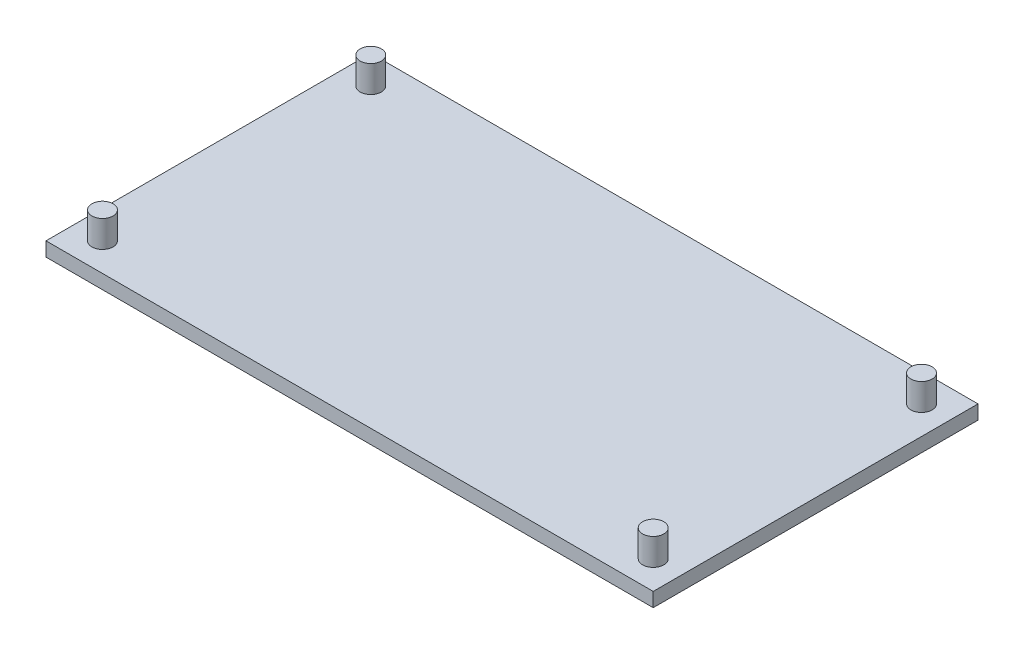
SolidWorks part; units mm, degrees
ref_plane "前视基准面" through (0, 0, 0) normal (0, 0, 1) x (1, 0, 0)
ref_plane "上视基准面" through (0, 0, 0) normal (0, 1, 0) x (1, 0, 0)
ref_plane "右视基准面" through (0, 0, 0) normal (1, 0, 0) x (0, 0, -1)
other "Configuration Table"
sketch "草图1" plane through (0, 0, 0) normal (0, 1, 0) x (1, 0, 0)
  line L5 (-43, -23) -> (43, -23)
  line L6 (-43, -23) -> (-43, 23)
  line L7 (-43, 23) -> (43, 23)
  line L8 (43, -23) -> (43, 23)
  line L9 (-43, -23) -> (43, 23) construction
  line L10 (-43, 23) -> (43, -23) construction
  point P0 (0, 0)
  dimension "D1" = 86
  dimension "D2" = 46
extrude "凸台-拉伸1" add sketch "草图1" along normal blind 2
sketch "草图2" plane through (0, 0, 0) normal (0, -1, 0) x (1, 0, 0)
  circle A0 centre (-39, 19) radius 1.5
  circle A1 centre (-39, -19) radius 1.5
  circle A2 centre (39, 19) radius 1.5
  circle A3 centre (39, -19) radius 1.5
  point P14 (0, 0)
  dimension "D1" = 3
extrude "凸台-拉伸2" add sketch "草图2" against normal blind 5.8
